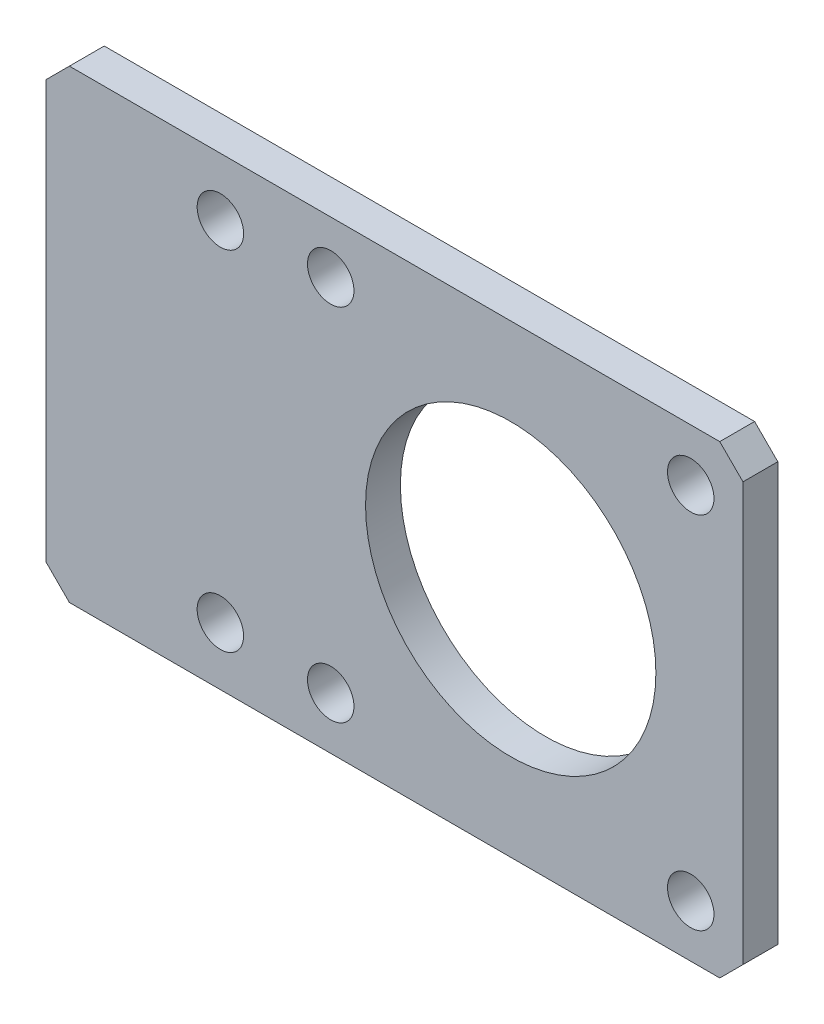
SolidWorks part; units mm, degrees
ref_plane "Front Plane" through (0, 0, 0) normal (0, 0, 1) x (1, 0, 0)
ref_plane "Top Plane" through (0, 0, 0) normal (0, 1, 0) x (1, 0, 0)
ref_plane "Right Plane" through (0, 0, 0) normal (1, 0, 0) x (0, 0, -1)
sketch "Sketch1" plane through (0, 0, 0) normal (0, 0, 1) x (1, 0, 0)
  line L1 (0, 0) -> (60, 0)
  line L2 (0, 0) -> (0, 40)
  line L3 (0, 40) -> (60, 40)
  line L4 (60, 0) -> (60, 40)
  dimension "D1" = 40
  dimension "D2" = 60
extrude "Boss-Extrude1" add sketch "Sketch1" along normal blind 3
sketch "Sketch2" plane through (0, 0, 3) normal (0, 0, 1) x (1, 0, 0)
  line L0 (0, 20) -> (60, 20) construction
  line L1 (0, 40) -> (0, 0) construction
  line L2 (60, 0) -> (60, 40) construction
  line L3 (15, 5) -> (15, 35) construction
  line L4 (24.5, 4.5) -> (55.5, 4.5) construction
  line L5 (24.5, 4.5) -> (24.5, 35.5) construction
  line L6 (24.5, 35.5) -> (55.5, 35.5) construction
  line L7 (55.5, 4.5) -> (55.5, 35.5) construction
  line L8 (24.5, 4.5) -> (55.5, 35.5) construction
  line L9 (24.5, 35.5) -> (55.5, 4.5) construction
  circle A0 centre (24.5, 35.5) radius 2
  circle A1 centre (55.5, 35.5) radius 2
  circle A2 centre (55.5, 4.5) radius 2
  circle A3 centre (24.5, 4.5) radius 2
  circle A4 centre (40, 20) radius 12.5
  circle A5 centre (15, 35) radius 2
  circle A6 centre (15, 5) radius 2
  point P6 (40, 20)
  point P20 (15, 20)
  dimension "D1" = 25
  dimension "D3" = 4
  dimension "D4" = 20
  dimension "D5" = 4
  dimension "D2" = 31
  dimension "D6" = 15
  dimension "D7" = 30
extrude "Cut-Extrude1" cut sketch "Sketch2" against normal through all
chamfer "Chamfer1" distance 2 angle 45 4 edges at (0, 0, 1.5) (60, 0, 1.5) (60, 40, 1.5) (0, 40, 1.5)
